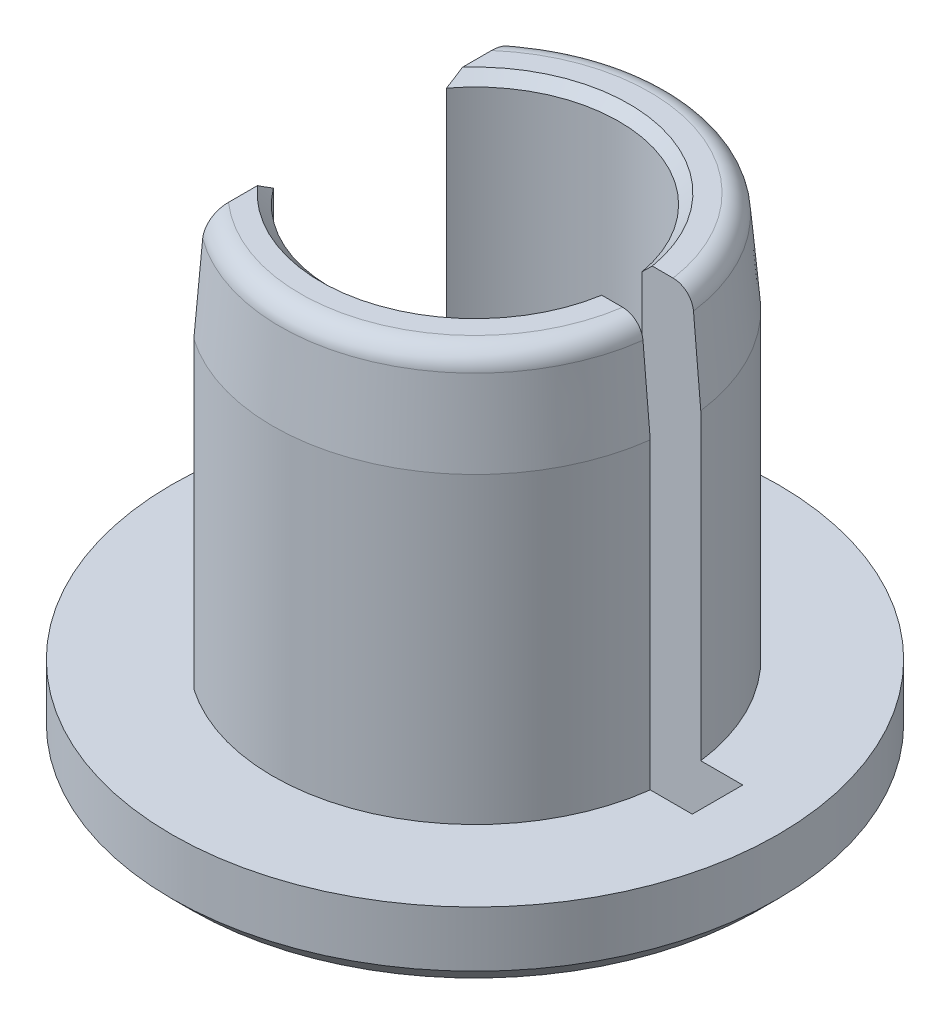
SolidWorks part; units mm, degrees
ref_plane "Front Plane" through (0, 0, 0) normal (0, 0, 1) x (1, 0, 0)
ref_plane "Top Plane" through (0, 0, 0) normal (0, 1, 0) x (1, 0, 0)
ref_plane "Right Plane" through (0, 0, 0) normal (1, 0, 0) x (0, 0, -1)
sketch "Sketch2" plane through (0, 0, 0) normal (0, 1, 0) x (-1, 0, 0)
  circle A0 centre (0, 0) radius 3
  dimension "D1" = 6
extrude "Boss-Extrude2" add sketch "Sketch2" along normal blind 0.75
sketch "Sketch3" plane through (0, 0.75, 0) normal (0, 1, 0) x (-1, 0, 0)
  line L0 (1.1386, 1.6442) -> (1.1386, -1.6442)
  arc A1 (1.1386, 1.6442) -> (1.1386, -1.6442) centre (0, 0) ccw
  dimension "D1" = 2
  dimension "D2" = 1.1386
extrude "Boss-Extrude3" add sketch "Sketch3" along normal blind 4
sketch "Croquis1" plane through (0, 4.75, 0) normal (0, 1, 0) x (1, 0, 0)
  circle A0 centre (0, 0) radius 1.425
  dimension "D1" = 2.85
extrude "Cortar-Extruir1" cut sketch "Croquis1" against normal through all
chamfer "Chaflán1" distance 0.2 angle 45 1 edges at (0, 0, 3)
chamfer "Chaflán2" distance 1 angle 5 1 edges at (2, 4.75, 0)
chamfer "Chaflán3" distance 0.1 angle 45 1 edges at (1.425, 4.75, 0)
fillet "Redondeo1" radius 0.2 1 edges at (1.9125, 4.75, 0)
sketch "Croquis2" plane through (0, 0, 0) normal (0, -1, 0) x (1, 0, 0)
  line L0 (0, 0) -> (50000, 0) construction
  line L1 (0.5543, 0.25) -> (2.4, 0.25)
  line L2 (0.5543, 0.25) -> (0.5543, -0.25)
  line L3 (0.5543, -0.25) -> (2.4, -0.25)
  line L4 (2.4, 0.25) -> (2.4, -0.25)
  line L5 (0.5543, 0.25) -> (2.4, -0.25) construction
  line L6 (0.5543, -0.25) -> (2.4, 0.25) construction
  point P0 (1.4771, 0)
  point P8 (0, 0)
  dimension "D1" = 2.4
  dimension "D2" = 0.5
extrude "Cortar-Extruir2" cut sketch "Croquis2" against normal through all
mirror "Simetría1" about plane through (0, 0, 0) normal (1, 0, 0) of "Cortar-Extruir2"
